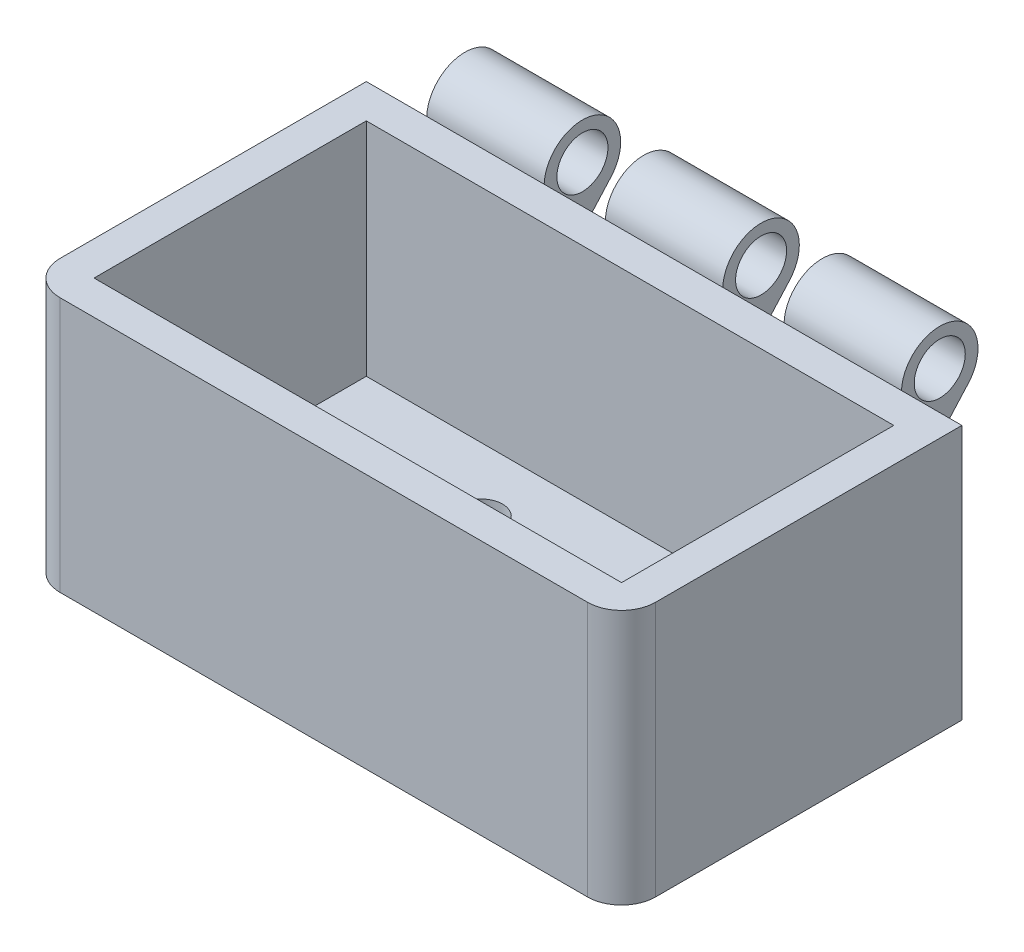
SolidWorks part; units mm, degrees
ref_plane "Front Plane" through (0, 0, 0) normal (0, 0, 1) x (1, 0, 0)
ref_plane "Top Plane" through (0, 0, 0) normal (0, 1, 0) x (1, 0, 0)
ref_plane "Right Plane" through (0, 0, 0) normal (1, 0, 0) x (0, 0, -1)
sketch "Sketch1" plane through (0, 0, 0) normal (0, 1, 0) x (1, 0, 0)
  line L1 (17.5, 10) -> (-17.5, 10)
  line L2 (17.5, 10) -> (17.5, -10)
  line L3 (17.5, -10) -> (-17.5, -10)
  line L4 (-17.5, 10) -> (-17.5, -10)
  line L5 (17.5, 10) -> (-17.5, -10) construction
  line L6 (17.5, -10) -> (-17.5, 10) construction
  point P0 (0, 0)
  dimension "D1" = 35
  dimension "D2" = 20
extrude "Boss-Extrude4" add sketch "Sketch1" along normal blind 15
shell "Shell2" thickness 2
ref_plane "Plane2" through (0, 15, 0) normal (0, 1, 0) x (1, 0, 0)
ref_plane "Plane3" through (13.95, 0, 0) normal (1, 0, 0) x (0, 0, -1)
sketch "Sketch8" plane through (13.95, 0, 0) normal (1, 0, 0) x (0, 0, -1)
  line L0 (13.9265, 13.4005) -> (10, 9)
  line L1 (10, 15) -> (10, 0) construction
  line L2 (10, 15) -> (10, 9)
  circle A0 centre (12.25, 14.9933) radius 1.5
  arc A2 (13.9265, 13.4005) -> (10, 15) centre (12.2477, 14.8985) ccw
  dimension "D1" = 3
  dimension "D2" = 6
extrude "Boss-Extrude7" add sketch "Sketch8" against normal blind 6.9
pattern_linear "LPattern4" count 3 spacing 10.5 along (-1, 0, 0) of "Boss-Extrude7"
ref_plane "Plane11" through (3.95, 0, 0) normal (1, 0, 0) x (0, 0, -1)
fillet "Fillet1" radius 2 2 edges at (-17.5, 7.5, 10) (17.5, 7.5, 10)
sketch "Sketch9" plane through (0, 0, 0) normal (0, 1, 0) x (1, 0, 0)
  circle A0 centre (-4.9975, 4.2505) radius 1.25
  point P2 (-4.8924, 4.2693)
  point P3 (-4.9975, 4.2505)
  dimension "D1" = 2.5
extrude "Cut-Extrude2" cut sketch "Sketch9" against normal blind 5 and the other way through all
sketch "Sketch10" plane through (0, 2, 0) normal (0, 1, 0) x (1, 0, 0)
  circle A0 centre (-5.0552, -0.5591) radius 1.25
  circle A1 centre (-4.9975, 4.2505) radius 1.25 construction
  point P4 (-5.2727, -0.4899)
  point P5 (-5.3507, -0.4914)
  point P6 (-5.3757, -0.4917)
  point P7 (-4.6921, -0.5365)
  point P8 (-4.8693, -0.5406)
  point P9 (-5.0202, -0.539)
  point P10 (-4.8924, -0.5407)
  point P11 (-5.0552, -0.5591)
  dimension "D1" = 4.81
  dimension "D2" = 2.5
extrude "Cut-Extrude3" cut sketch "Sketch10" against normal through all
mirror "Mirror1" about plane through (0, 0, 0) normal (1, 0, 0) of "Cut-Extrude3", "Cut-Extrude2"
